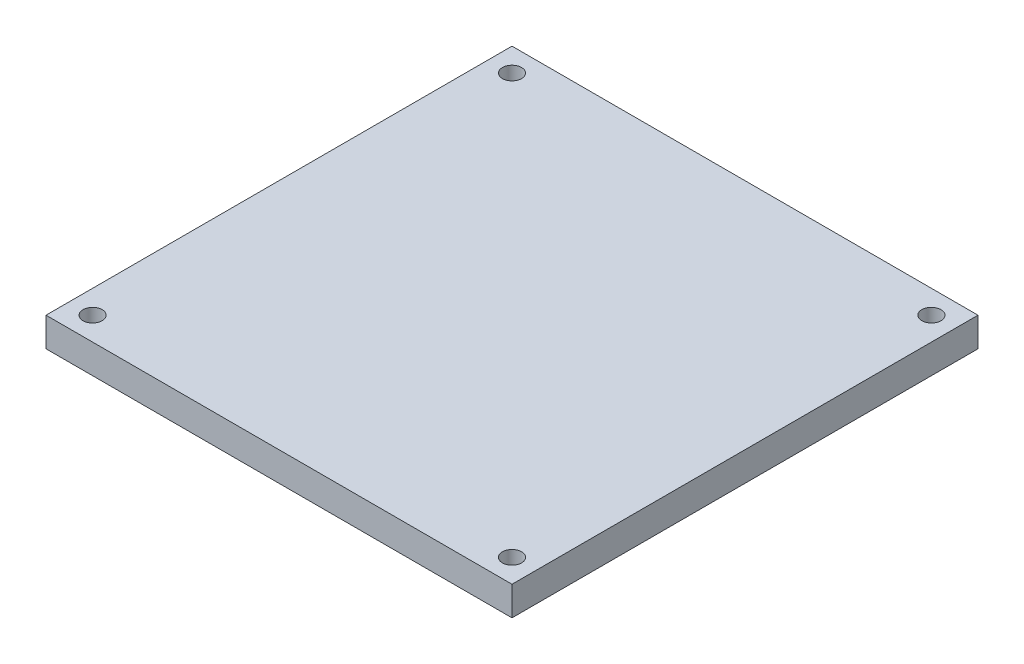
SolidWorks part; units mm, degrees
material "PVC rigide"
ref_plane "Plan de face" through (0, 0, 0) normal (0, 0, 1) x (1, 0, 0)
ref_plane "Plan de dessus" through (0, 0, 0) normal (0, 1, 0) x (1, 0, 0)
ref_plane "Plan de droite" through (0, 0, 0) normal (1, 0, 0) x (0, 0, -1)
sketch "Esquisse1" plane through (0, 0, 0) normal (0, 1, 0) x (1, 0, 0)
  line L0 (0, 0) -> (0, 40) construction
  line L1 (-40, 40) -> (40, 40)
  line L2 (-40, 40) -> (-40, -40)
  line L3 (-40, -40) -> (40, -40)
  line L4 (40, 40) -> (40, -40)
  line L5 (0, 0) -> (40, 0) construction
  circle A0 centre (-36, 36) radius 1.65
  circle A1 centre (36, 36) radius 1.65
  circle A2 centre (-36, -36) radius 1.65
  circle A3 centre (36, -36) radius 1.65
  dimension "D4" = 3.3
  dimension "D1" = 80
  dimension "D2" = 4
  dimension "D3" = 4
extrude "Extrusion1" add sketch "Esquisse1" along normal blind 5
